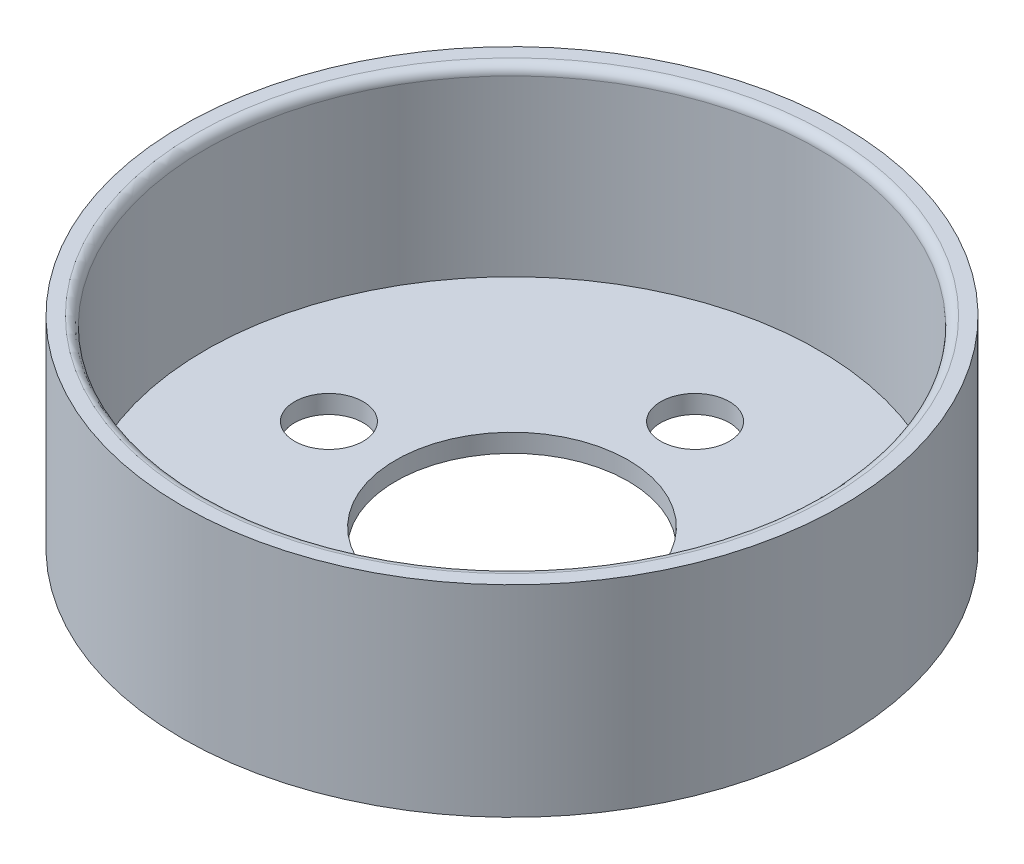
SolidWorks part; units mm, degrees
ref_plane "Front Plane" through (0, 0, 0) normal (0, 0, 1) x (1, 0, 0)
ref_plane "Top Plane" through (0, 0, 0) normal (0, 1, 0) x (1, 0, 0)
ref_plane "Right Plane" through (0, 0, 0) normal (1, 0, 0) x (0, 0, -1)
sketch "Sketch1" plane through (0, 0, 0) normal (0, 1, 0) x (1, 0, 0)
  circle A0 centre (0, 0) radius 42.545
  circle A1 centre (0, 0) radius 45.72
  dimension "D1" = 85.09
  dimension "D2" = 3.175
extrude "Boss-Extrude1" add sketch "Sketch1" along normal blind 2.54 contours A0 | A1 A0
sketch "Sketch2" plane through (0, 2.54, 0) normal (0, 1, 0) x (1, 0, 0)
  circle A0 centre (0, 0) radius 45.72 construction
  circle A1 centre (0, 0) radius 45.72
  circle A2 centre (0, 0) radius 42.545
  dimension "D1" = 85.09
extrude "Boss-Extrude2" add sketch "Sketch2" along normal blind 25.4
sketch "Sketch3" plane through (0, 0, 0) normal (0, -1, 0) x (1, 0, 0)
  circle A0 centre (0, 0) radius 16.129
  dimension "D1" = 32.258
extrude "Cut-Extrude1" cut sketch "Sketch3" against normal up to next
fillet "Fillet1" radius 1.27 1 edges at (0, 27.94, 42.545)
sketch "Sketch5" plane through (0, 2.54, 0) normal (0, 1, 0) x (1, 0, 0)
  circle A0 centre (0, 25.4) radius 4.7625
  circle A1 centre (0, 0) radius 16.129 construction
  point P2 (0, 0)
  dimension "D1" = 9.525
  dimension "D2" = 25.4
extrude "Cut-Extrude2" cut sketch "Sketch5" against normal up to next
pattern_circular "CirPattern1" count 4 over 360 about axis through (0, 0, 0) along (0, 1, 0) of "Cut-Extrude2"
